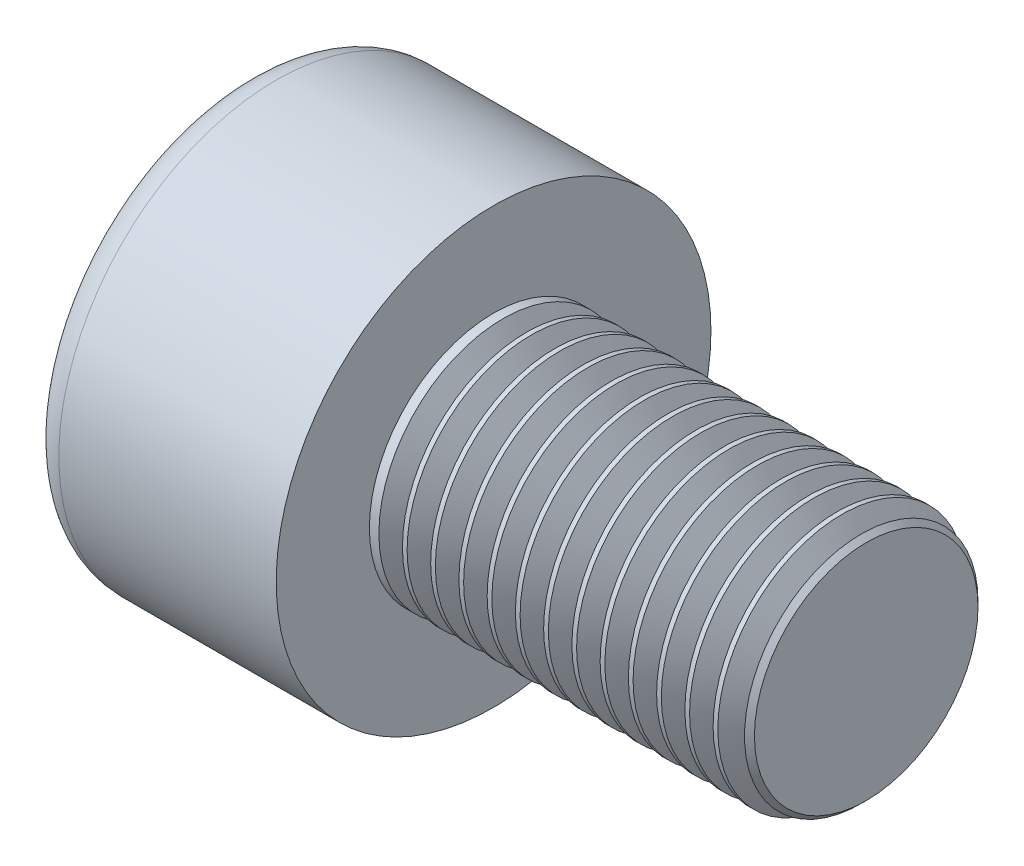
SolidWorks part; units mm, degrees
ref_plane "Front" through (0, 0, 0) normal (0, 0, 1) x (1, 0, 0)
ref_plane "Top" through (0, 0, 0) normal (0, 1, 0) x (1, 0, 0)
ref_plane "Right" through (0, 0, 0) normal (1, 0, 0) x (0, 0, -1)
sketch "Sketch1" plane through (0, 0, 0) normal (1, 0, 0) x (0, 0, -1)
  circle A0 centre (0, 0) radius 3.5
  dimension "dk" = 7
extrude "BaseHead" add sketch "Sketch1" along normal blind 4
sketch "Sketch2" plane through (4, 0, 0) normal (1, 0, 0) x (0, 0, -1)
  circle A0 centre (0, 0) radius 2
  dimension "d" = 4
extrude "BaseBody" add sketch "Sketch2" along normal blind 6
cosmetic thread "ThreadCosmetic1" [suppressed] parameters "b"=6, "D2"=3.242
sketch "Sketch3" plane through (0, 0, 0) normal (1, 0, 0) x (0, 0, -1)
  line L1 (1.7321, 0) -> (0.866, 1.5)
  line L2 (0.866, 1.5) -> (-0.866, 1.5)
  line L3 (-0.866, 1.5) -> (-1.7321, 0)
  line L4 (-1.7321, 0) -> (-0.866, -1.5)
  line L5 (-0.866, -1.5) -> (0.866, -1.5)
  line L6 (0.866, -1.5) -> (1.7321, 0)
  circle A0 centre (0, 0) radius 1.5 construction
  dimension "s" = 3
  dimension "e" = 3.4641
extrude "HexagonSocket" cut sketch "Sketch3" along normal blind 2
sketch "Sketch4" plane through (-4.1961, 0.75, 0) normal (0, 0, 1) x (-1, 0, 0)
  line L0 (-6.1961, 2.25) -> (-7.0622, 0.75)
  line L2 (-7.0622, 0.75) -> (-6.1961, 0.75)
  line L3 (-6.1961, 0.75) -> (-6.1961, 2.25)
  line L4 (-5.0351, 0.75) -> (0.839, 0.75) construction
  line L5 (-14.1961, 0.75) -> (-8.1961, 0.75) construction
  line L6 (-8.1961, 0.75) -> (-4.1961, 0.75) construction
  dimension "m" = 60
revolve "Cut-Revolve1" cut sketch "Sketch4" angle 360 about L4
fillet "HeadFillet" [suppressed] radius 0.2
fillet "TopFillet" radius 0.5 1 edges at (0, 0, -3.5)
chamfer "Chamfer1" distance 0.2 angle 45 1 edges at (10, 0, -2)
sketch "Sketch5" plane through (0, 0, 0) normal (0, 0, 1) x (1, 0, 0)
  line L0 (9.8, 1.6718) -> (9.9895, 2)
  line L1 (9.9895, 2) -> (9.9895, 2.379)
  line L2 (9.9895, 2.379) -> (9.6105, 2.379)
  line L3 (9.6105, 2.379) -> (9.6105, 2)
  line L4 (9.6105, 2) -> (9.8, 1.6718)
  line L5 (0, 0) -> (7.8886, 0) construction
  line L6 (9.8, -2) -> (9.8, 2) construction
  dimension "D1" = 4
  dimension "D2" = 0.379
revolve "Cut-Revolve10" cut sketch "Sketch5" angle 360 about L5
pattern_linear "LPattern10" count 13 spacing 0.4548 along (-1, 0, 0) of "Cut-Revolve10"
equation "\"r1@TopFillet\" = \"d@Sketch2\" / 8"
equation "\"D1@Chamfer1\" = \"r@HeadFillet\""
equation "\"D1@Sketch5\" = \"d@Sketch2\""
equation "\"D2@Sketch5\" =  ( \"d@Sketch2\" - \"D2@ThreadCosmetic1\" )  / 2"
equation "\"D3@LPattern10\" = \"D2@Sketch5\" * 1.2"
equation "\"D1@LPattern10\" = \"b@ThreadCosmetic1\" / \"D3@LPattern10\""
